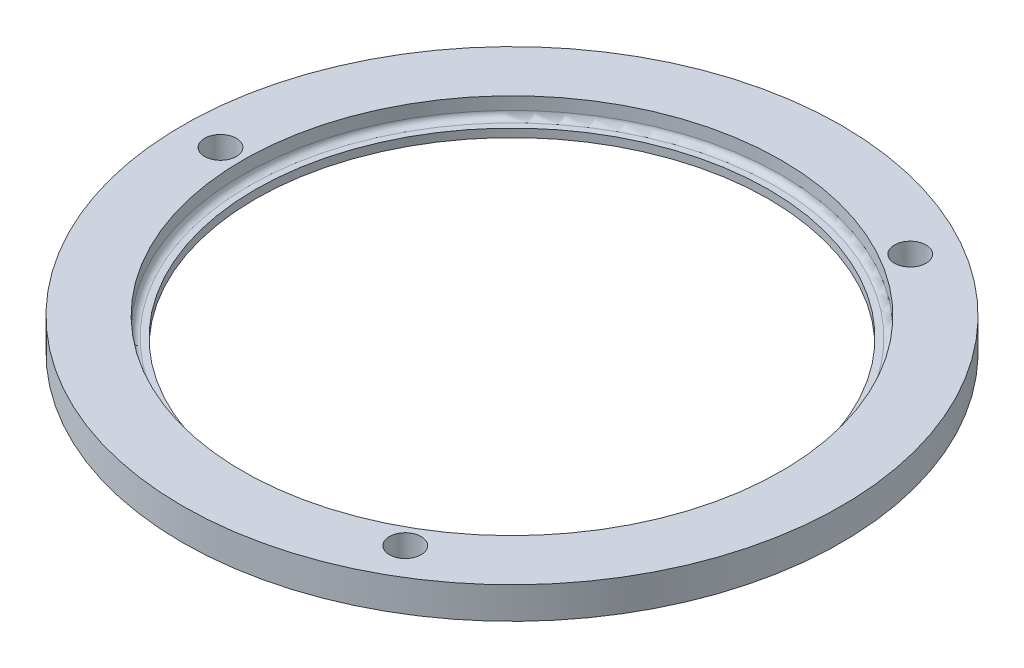
SolidWorks part; units mm, degrees
ref_plane "Plano frontal" through (0, 0, 0) normal (0, 0, 1) x (1, 0, 0)
ref_plane "Plano superior" through (0, 0, 0) normal (0, 1, 0) x (1, 0, 0)
ref_plane "Plano direito" through (0, 0, 0) normal (1, 0, 0) x (0, 0, -1)
sketch "Esboço1" plane through (0, 0, 0) normal (0, 0, 1) x (1, 0, 0)
  line L0 (0, -12.6427) -> (0, 15.0833) construction
  line L1 (52, 4.1491) -> (52, -0.8509)
  line L2 (42.5, -0.1509) -> (40.5, -0.1509)
  line L3 (40.5, -0.1509) -> (40.5, 1.1491)
  line L4 (40.5, 1.1491) -> (42.5, 1.1491)
  line L5 (42.5, 1.1491) -> (42.5, 4.1491)
  line L6 (42.5, 4.1491) -> (52, 4.1491)
  arc A0 (42.5, -0.1509) -> (52, -0.8509) centre (47.8961, 8.2683) ccw
  dimension "D8" = 10
  dimension "D1" = 40.5
  dimension "D2" = 42.5
  dimension "D3" = 52
  dimension "D4" = 42.5
  dimension "D5" = 5
  dimension "D6" = 3
  dimension "D7" = 1.3
revolve "Revolução1" add sketch "Esboço1" angle 360 about L0
fillet "Filete1" radius 1 1 edges at (0, 1.1491, -42.5)
fillet "Filete2" radius 2 1 edges at (0, -0.1509, -42.5)
sketch "Esboço2" plane through (0, 4.1491, 0) normal (0, 1, 0) x (1, 0, 0)
  circle A0 centre (0, 0) radius 46 construction
  circle A1 centre (-46, 0) radius 2.5
  circle A2 centre (23, 39.8372) radius 2.5
  circle A3 centre (23, -39.8372) radius 2.5
  point P11 (0, 0)
  dimension "D1" = 92
  dimension "D2" = 5
  dimension "D3" = 3
extrude "Corte-extrusão1" cut sketch "Esboço2" against normal through all
